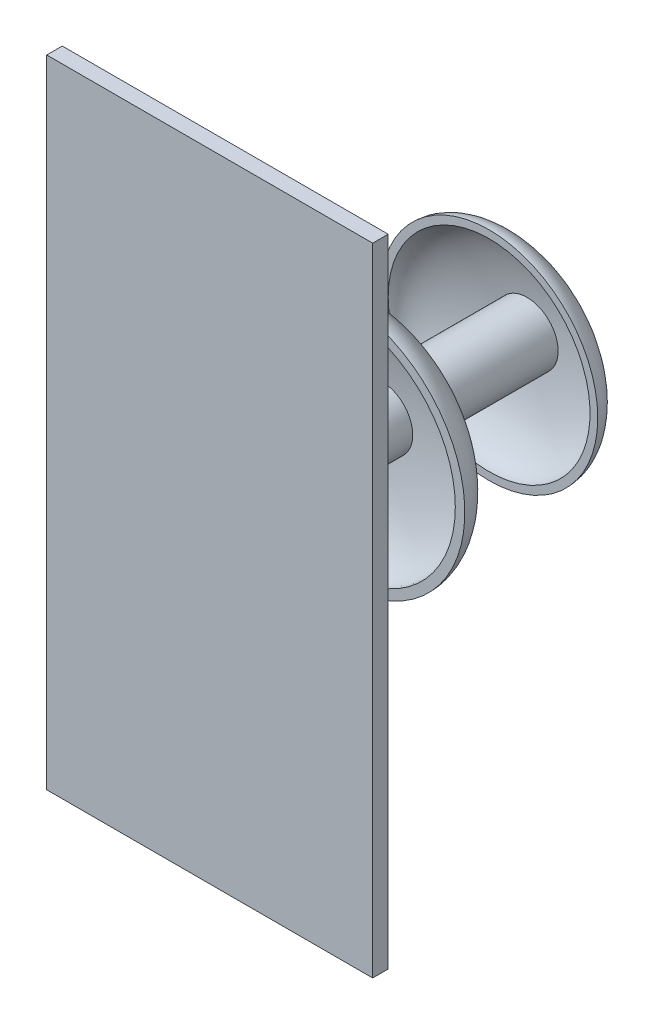
SolidWorks part; units mm, degrees
ref_plane "Plan de face" through (0, 0, 0) normal (0, 0, 1) x (1, 0, 0)
ref_plane "Plan de dessus" through (0, 0, 0) normal (0, 1, 0) x (1, 0, 0)
ref_plane "Plan de droite" through (0, 0, 0) normal (1, 0, 0) x (0, 0, -1)
sketch "Esquisse1" plane through (0, 0, 0) normal (0, 0, 1) x (1, 0, 0)
  line L1 (0, 0) -> (2.1, 0)
  line L2 (0, 0) -> (0, 4.1)
  line L3 (0, 4.1) -> (2.1, 4.1)
  line L4 (2.1, 0) -> (2.1, 4.1)
  dimension "D1" = 2.1
  dimension "D2" = 4.1
extrude "Boss.-Extru.1" add sketch "Esquisse1" along normal blind 0.1
sketch "Esquisse4" plane through (0, 0, 0.1) normal (0, 0, 1) x (1, 0, 0)
  line L0 (0, 4.1) -> (2.1, 0) construction
  line L1 (2.1, 4.1) -> (0, 0) construction
  point P8 (1.05, 2.05)
ref_plane "Plan1" through (0, 2.05, 0) normal (0, 1, 0) x (1, 0, 0)
sketch "Esquisse7" plane through (0, 2.05, 0) normal (0, 1, 0) x (1, 0, 0)
  line L0 (1.05, -0.1) -> (1.05, 1.4839) construction
  line L1 (1.05, 0.7436) -> (2.65, 0.7436) construction
  line L2 (1.05, 1.7) -> (1.75, 1.7) construction
  line L4 (1.25, 0.396) -> (1.25, 0)
  line L5 (2.1, 0) -> (0, 0) construction
  line L6 (1.05, 1.4839) -> (1.05, 2.8661) construction
  line L7 (1.05, 2) -> (1.05, 0)
  line L8 (1.25, 0) -> (1.05, 0)
  line L9 (1.25, 1.4028) -> (1.25, 1.1067)
  line L10 (1.7888, 0.7436) -> (1.85, 0.7436)
  line L11 (1.25, 0.396) -> (1.25, 1.008)
  line L12 (1.7002, 1.7) -> (1.75, 1.7)
  line L13 (1.25, 1.4028) -> (1.25, 1.9448)
  ellipse E0 centre (1.05, 1.7) end of major axis (1.75, 1.7) minor radius 0.3 (1.75, 1.7) -> (1.05, 2) ccw
  ellipse E1 centre (1.05, 0.7436) end of major axis (1.85, 0.7436) minor radius 0.375 (1.85, 0.7436) -> (1.25, 1.1067) ccw
  ellipse E2 centre (1.05, 0.7436) end of major axis (1.7888, 0.7436) minor radius 0.2746 (1.7888, 0.7436) -> (1.25, 1.008) ccw
  ellipse E3 centre (1.05, 1.7) end of major axis (1.7002, 1.7) minor radius 0.2573 (1.7002, 1.7) -> (1.25, 1.9448) ccw
  dimension "D1" = 2
  dimension "D2" = 0.3
  dimension "D3" = 0.75
  dimension "D4" = 0.2
  dimension "D5" = 1.6
  dimension "D6" = 1.4
  dimension "D7" = 0.396
  dimension "D8" = 0.2961
  dimension "D9" = 0.7436
  dimension "D10" = 0.612
  dimension "D11" = 0.7388
  dimension "D12" = 0.2
  dimension "D13" = 0.6502
  dimension "D14" = 0.2448
revolve "Révolution1" add sketch "Esquisse7" angle 360 about L7
